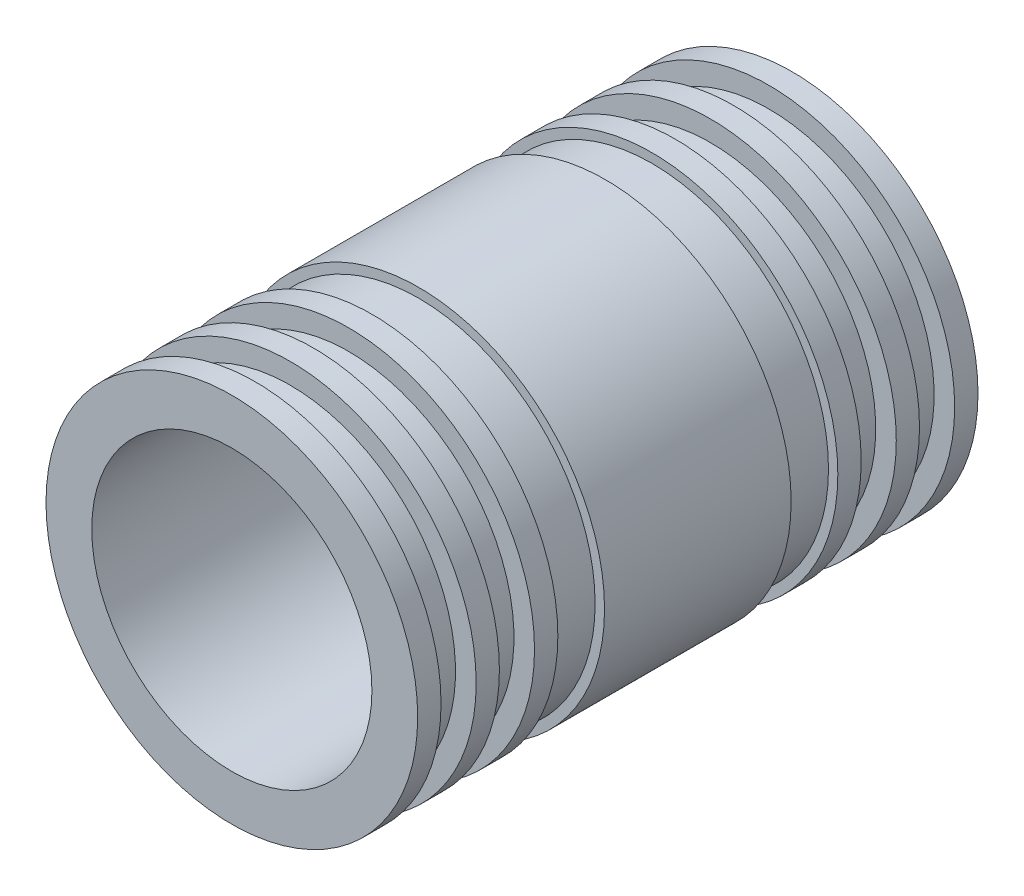
SolidWorks part; units mm, degrees
material "6061 Alloy"
ref_plane "Front Plane" through (0, 0, 0) normal (0, 0, 1) x (1, 0, 0)
ref_plane "Top Plane" through (0, 0, 0) normal (0, 1, 0) x (1, 0, 0)
ref_plane "Right Plane" through (0, 0, 0) normal (1, 0, 0) x (0, 0, -1)
sketch "Sketch1" plane through (0, 0, 0) normal (0, 0, 1) x (1, 0, 0)
  circle A0 centre (0, 0) radius 25.273
  dimension "D1" = 50.546
extrude "Boss-Extrude1" add sketch "Sketch1" along normal blind 76.2
sketch "Sketch5" plane through (0, 0, 76.2) normal (0, 0, 1) x (1, 0, 0)
  circle A0 centre (0, 0) radius 19.05
  dimension "D1" = 38.1
extrude "Cut-Extrude2" cut sketch "Sketch5" against normal blind 76.2
ref_plane "Plane1" through (0, 0, 76.2) normal (-1, 0, 0) x (0, 1, 0)
ref_plane "Plane2" through (0, 0, 76.2) normal (-1, 0, 0) x (0, 1, 0)
ref_plane "Plane3" through (0, 0, 76.2) normal (-1, 0, 0) x (0, 1, 0)
ref_plane "Plane4" through (0, 0, 76.2) normal (-1, 0, 0) x (0, 1, 0)
sketch "Groove" plane through (0, 0, 0) normal (1, 0, 0) x (0, 0, -1)
  line L0 (0, 25.273) -> (-76.2, 25.273) construction
  line L1 (-76.2, 25.273) -> (-76.2, -25.273) construction
  line L2 (-73.025, 25.273) -> (-73.025, 22.479)
  line L3 (-73.025, 22.479) -> (-68.2625, 22.479)
  line L4 (-68.2625, 22.479) -> (-68.2447, 25.273)
  line L5 (-68.2447, 25.273) -> (-65.0875, 25.273)
  line L6 (-65.0875, 25.273) -> (-65.0875, 22.479)
  line L7 (-65.0875, 22.479) -> (-60.3123, 22.479)
  line L8 (-60.3123, 22.479) -> (-60.3123, 25.273)
  line L9 (-60.3123, 25.273) -> (-57.1373, 25.273)
  line L10 (-57.1373, 25.273) -> (-57.1373, 24.003)
  line L11 (-57.1373, 24.003) -> (-50.8, 24.003)
  line L12 (-50.8, 24.003) -> (-50.7873, 25.273)
  line L13 (-50.7873, 25.273) -> (-50.7873, 27.7239)
  line L14 (-50.7873, 27.7239) -> (-73.025, 27.7239)
  line L15 (-73.025, 27.7239) -> (-73.025, 25.273)
  line L16 (-38.1, 25.273) -> (-38.1, -25.3913) construction
  line L17 (-3.175, 27.7239) -> (-3.175, 25.273)
  line L18 (-25.4127, 27.7239) -> (-3.175, 27.7239)
  line L19 (-25.4127, 25.273) -> (-25.4127, 27.7239)
  line L20 (-25.4, 24.003) -> (-25.4127, 25.273)
  line L21 (-19.0627, 24.003) -> (-25.4, 24.003)
  line L22 (-19.0627, 25.273) -> (-19.0627, 24.003)
  line L23 (-15.8877, 25.273) -> (-19.0627, 25.273)
  line L24 (-15.8877, 22.479) -> (-15.8877, 25.273)
  line L25 (-11.1125, 22.479) -> (-15.8877, 22.479)
  line L26 (-11.1125, 25.273) -> (-11.1125, 22.479)
  line L27 (-7.9553, 25.273) -> (-11.1125, 25.273)
  line L28 (-7.9375, 22.479) -> (-7.9553, 25.273)
  line L29 (-3.175, 22.479) -> (-7.9375, 22.479)
  line L30 (-3.175, 25.273) -> (-3.175, 22.479)
  point P0 (-73.025, 25.273)
  point P1 (-68.2625, 25.273)
  point P4 (-68.2447, 25.273)
  point P5 (-65.0875, 25.273)
  point P7 (-60.3123, 25.273)
  point P9 (-57.1373, 25.273)
  point P10 (-50.7873, 25.273)
  point P11 (-50.8, 25.273)
  point P14 (-38.1, 25.273)
  point P27 (-38.1, -25.3913)
  point P44 (-25.4, 25.273)
  point P45 (-7.9375, 25.273)
  dimension "D1" = 3.175
  dimension "D2" = 4.7625
  dimension "D3" = 3.175
  dimension "D4" = 4.7752
  dimension "D5" = 3.175
  dimension "D6" = 2.794
  dimension "D7" = 25.4
  dimension "D8" = 2.794
  dimension "D9" = 1.27
ref_plane "Plane9" through (0, 0, 60.3123) normal (0, 0, 1) x (1, 0, 0)
sketch "groove path" plane through (0, 0, 60.3123) normal (0, 0, 1) x (1, 0, 0)
  circle A0 centre (0, 0) radius 25.273 construction
  circle A1 centre (0, 0) radius 25.273
sweep "Cut-Sweep4" cut profiles "Groove" path "groove path"
sketch "Sketch6" plane through (0, 0, 0) normal (0, 1, 0) x (1, 0, 0)
  line L0 (-19.05, -76.2) -> (19.05, -76.2) construction
  line L1 (19.05, 0) -> (-19.05, 0) construction
  point P0 (0, -38.1)
  point P1 (0, -22.225)
  point P2 (0, -53.975)
  dimension "D1" = 38.1
  dimension "D2" = 22.225
  dimension "D3" = 22.225
